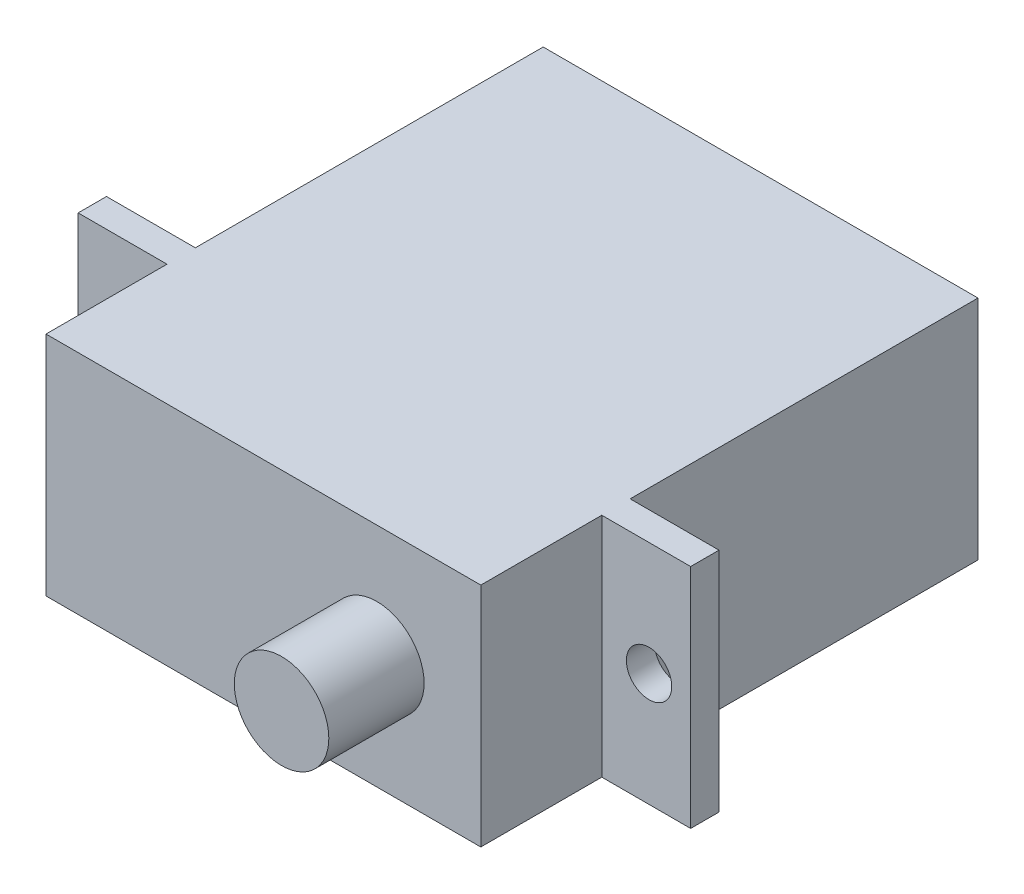
SolidWorks part; units mm, degrees
ref_plane "前视基准面" through (0, 0, 0) normal (0, 0, 1) x (1, 0, 0)
ref_plane "上视基准面" through (0, 0, 0) normal (0, 1, 0) x (1, 0, 0)
ref_plane "右视基准面" through (0, 0, 0) normal (1, 0, 0) x (0, 0, -1)
sketch "草图1" plane through (0, 0, 0) normal (0, 0, 1) x (1, 0, 0)
  line L1 (-16.2, 6) -> (16.2, 6)
  line L2 (-16.2, 6) -> (-16.2, -6)
  line L3 (-16.2, -6) -> (16.2, -6)
  line L4 (16.2, 6) -> (16.2, -6)
  line L5 (0, -6) -> (0, 6) construction
  line L6 (-16.2, 0) -> (16.2, 0) construction
  circle A0 centre (-14, 0) radius 1.2
  circle A1 centre (14, 0) radius 1.2
  point P1 (0, 0)
  dimension "D4" = 2.4
  dimension "D1" = 32.4
  dimension "D2" = 12
  dimension "D3" = 28
extrude "凸台-拉伸1" add sketch "草图1" along normal blind 1.5
sketch "草图2" plane through (0, 0, 1.5) normal (0, 0, 1) x (1, 0, 0)
  line L1 (-11.5, 6) -> (11.5, 6)
  line L2 (-11.5, 6) -> (-11.5, -6)
  line L3 (-11.5, -6) -> (11.5, -6)
  line L4 (11.5, 6) -> (11.5, -6)
  line L5 (0, -6) -> (0, 6) construction
  line L6 (-11.5, 0) -> (11.5, 0) construction
  point P1 (0, 0)
  dimension "D1" = 23
  dimension "D2" = 12
extrude "凸台-拉伸2" add sketch "草图2" along normal blind 6.4 and the other way blind 19.9
sketch "草图3" plane through (0, 0, 7.9) normal (0, 0, 1) x (1, 0, 0)
  line L0 (11.5, -6) -> (11.5, 6) construction
  circle A0 centre (6, 0) radius 2.5
  dimension "D1" = 5
  dimension "D2" = 5.5
extrude "凸台-拉伸3" add sketch "草图3" along normal blind 5.04
